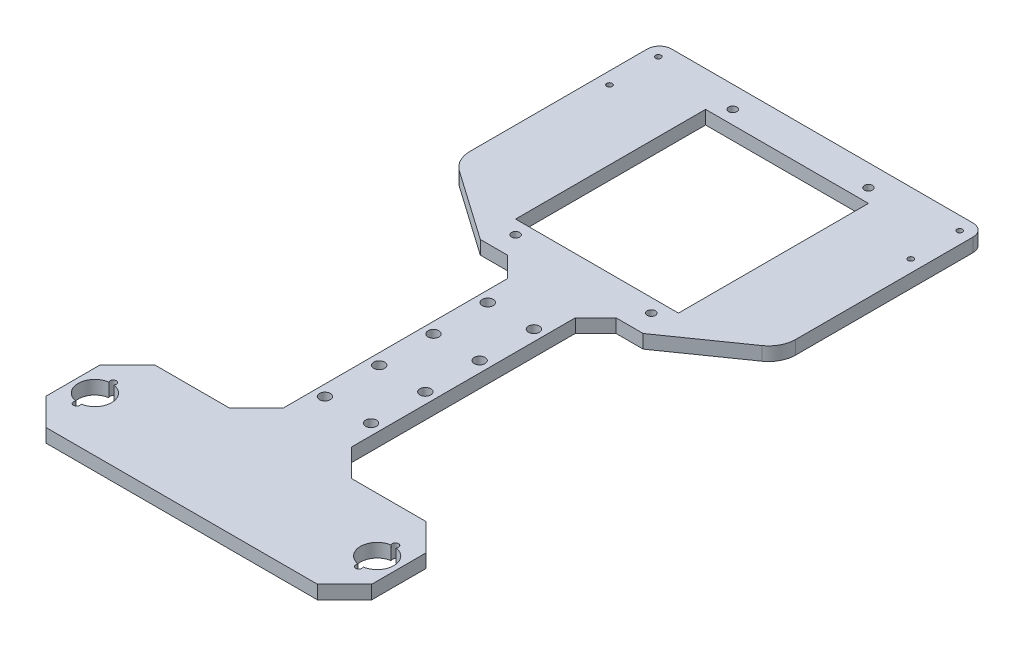
SolidWorks part; units mm, degrees
material "Acrílico (médio-alto impacto)"
ref_plane "Plano frontal" through (0, 0, 0) normal (0, 0, 1) x (1, 0, 0)
ref_plane "Plano superior" through (0, 0, 0) normal (0, 1, 0) x (1, 0, 0)
ref_plane "Plano direito" through (0, 0, 0) normal (1, 0, 0) x (0, 0, -1)
sketch "Esboço1" plane through (0, 0, 0) normal (0, 1, 0) x (1, 0, 0)
  line L0 (-18.0889, 17.9415) -> (-18.0889, 19.4415)
  line L1 (-13.5889, 23.9415) -> (97.4111, 23.9415)
  line L2 (-18.0889, 17.9415) -> (-18.0889, -45.8529)
  line L3 (-13.8247, -54.0444) -> (11.9111, -72.0648)
  line L4 (11.9111, -72.0648) -> (21.9111, -72.0648)
  line L5 (41.9111, -1077.9191) -> (41.9111, -72.0648) construction
  line L7 (97.6469, -54.0444) -> (71.9111, -72.0648)
  line L9 (101.9111, 17.9415) -> (101.9111, -45.8529)
  line L10 (101.9111, 17.9415) -> (101.9111, 19.4415)
  line L11 (21.9111, -72.0648) -> (29.4111, -79.5648)
  line L12 (29.4111, -79.5648) -> (29.4111, -162.0648)
  line L13 (29.4111, -162.0648) -> (19.4111, -172.0648)
  line L14 (19.4111, -172.0648) -> (-8.0889, -172.0648)
  line L15 (-18.0889, -182.0648) -> (-18.0889, -202.0648)
  line L16 (-8.0889, -212.0648) -> (91.9111, -212.0648)
  line L17 (-18.0889, -202.0648) -> (-8.0889, -212.0648)
  line L18 (-8.0889, -172.0648) -> (-18.0889, -182.0648)
  line L19 (71.9111, -72.0648) -> (61.9111, -72.0648)
  line L20 (41.9111, 23.9415) -> (41.9111, 1029.7958) construction
  line L21 (61.9111, -72.0648) -> (54.4111, -79.5648)
  line L22 (91.9111, -172.0648) -> (101.9111, -182.0648)
  line L23 (101.9111, -202.0648) -> (91.9111, -212.0648)
  line L24 (101.9111, -182.0648) -> (101.9111, -202.0648)
  line L25 (64.4111, -172.0648) -> (91.9111, -172.0648)
  line L26 (54.4111, -162.0648) -> (64.4111, -172.0648)
  line L27 (54.4111, -79.5648) -> (54.4111, -162.0648)
  arc A0 (-13.5889, 23.9415) -> (-18.0889, 19.4415) centre (-13.5889, 19.4415) ccw
  arc A1 (97.4111, 23.9415) -> (101.9111, 19.4415) centre (97.4111, 19.4415) cw
  arc A2 (97.6469, -54.0444) -> (101.9111, -45.8529) centre (91.9111, -45.8529) ccw
  arc A3 (-18.0889, -45.8529) -> (-13.8247, -54.0444) centre (-8.0889, -45.8529) ccw
  point P10 (101.9111, -51.0585)
  point P18 (-18.0889, -51.0585)
  point P20 (41.9111, -72.0648)
  point P22 (41.9111, 23.9415)
  point P26 (-18.0889, -212.0648)
  point P28 (-18.0889, -172.0648)
  point P37 (41.9111, -212.0648)
  point P43 (101.9111, -172.0648)
  point P44 (101.9111, -212.0648)
  dimension "D5" = 10
  dimension "D1" = 75
  dimension "D2" = 125
  dimension "D3" = 30
  dimension "D4" = 45
  dimension "D6" = 120
  dimension "D7" = 25
  dimension "D8" = 90
  dimension "D9" = 45
  dimension "D10" = 10
  dimension "D11" = 180
  dimension "D12" = 40
extrude "Base " add sketch "Esboço1" along normal blind 5 contours L9 A2 L7 L19 L21 L27 L26 L25 L22 L24 L23 L16 L17 L15 L18 L14 L13 L12 L11 L4 L3 A3 L2 L0 A0 L1 A1 L10
sketch "Esboço2" plane through (0, 5, 0) normal (0, 1, 0) x (1, 0, 0)
  line L0 (-13.5889, 23.9415) -> (97.4111, 23.9415) construction
  line L1 (-18.0889, -45.8529) -> (-18.0889, 19.4415) construction
  line L2 (41.9111, 23.9415) -> (41.9111, -27.3922) construction
  circle A0 centre (-13.5889, 19.0215) radius 1
  circle A1 centre (-13.5889, 1.0215) radius 1
  circle A2 centre (97.4111, 1.0215) radius 1
  circle A3 centre (97.4111, 19.0215) radius 1
  dimension "D1" = 4.92
  dimension "D2" = 4.5
  dimension "D3" = 2
  dimension "D4" = 2
  dimension "D5" = 4.5
  dimension "D6" = 18
extrude "Furo Bracket Motor" cut sketch "Esboço2" against normal blind 3
sketch "Esboço4" plane through (0, 0, 0) normal (0, -1, 0) x (1, 0, 0)
  line L1 (11.9111, 59.0635) -> (71.9111, 59.0635)
  line L2 (11.9111, 59.0635) -> (11.9111, -10.9365)
  line L3 (11.9111, -10.9365) -> (71.9111, -10.9365)
  line L4 (71.9111, 59.0635) -> (71.9111, -10.9365)
  line L5 (101.9111, -19.4415) -> (101.9111, 45.8529) construction
  line L7 (-13.5889, -23.9415) -> (97.4111, -23.9415) construction
  line L8 (-18.0889, -19.4415) -> (-18.0889, 45.8529) construction
  dimension "D1" = 60
  dimension "D2" = 70
  dimension "D3" = 30
  dimension "D4" = 13.005
  dimension "D5" = 30
extrude "Encaixe PCB" cut sketch "Esboço4" against normal through all
sketch "Esboço6" plane through (0, 0, 0) normal (0, -1, 0) x (1, 0, 0)
  line L0 (71.9111, 59.0635) -> (11.9111, 59.0635) construction
  line L1 (11.9111, 59.0635) -> (11.9111, -10.9365) construction
  line L2 (71.9111, -10.9365) -> (71.9111, 59.0635) construction
  line L3 (11.9111, -10.9365) -> (71.9111, -10.9365) construction
  circle A0 centre (16.9111, 64.0635) radius 1.5
  circle A1 centre (66.9111, 64.0635) radius 1.5
  circle A2 centre (66.9111, -15.9365) radius 1.5
  circle A3 centre (16.9111, -15.9365) radius 1.5
  dimension "D1" = 5
  dimension "D2" = 5
  dimension "D3" = 5
  dimension "D4" = 5
  dimension "D5" = 5
  dimension "D6" = 5
  dimension "D7" = 5
  dimension "D8" = 5
  dimension "D9" = 3
  dimension "D10" = 3
  dimension "D11" = 3
  dimension "D12" = 3
extrude "Parafuso PCB" cut sketch "Esboço6" against normal through all
sketch "Esboço7" plane through (0, 0, 0) normal (0, -1, 0) x (1, 0, 0)
  line L0 (29.4111, 79.5648) -> (29.4111, 162.0648) construction
  line L1 (41.9111, 212.0648) -> (41.9111, -23.9415) construction
  circle A0 centre (33.4111, 90.8148) radius 2
  circle A1 centre (33.4111, 110.8148) radius 2
  circle A2 centre (33.4111, 130.8148) radius 2
  circle A3 centre (33.4111, 150.8148) radius 2
  circle A4 centre (50.4111, 150.8148) radius 2
  circle A5 centre (50.4111, 130.8148) radius 2
  circle A6 centre (50.4111, 110.8148) radius 2
  circle A7 centre (50.4111, 90.8148) radius 2
  dimension "D1" = 11.25
  dimension "D2" = 20
  dimension "D3" = 20
  dimension "D4" = 20
  dimension "D5" = 11.25
  dimension "D6" = 4
  dimension "D7" = 4
  dimension "D8" = 4
  dimension "D9" = 4
  dimension "D10" = 4
  dimension "D11" = 4
extrude "Enforca Gato" cut sketch "Esboço7" against normal through all
sketch "Esboço8" plane through (0, 0, 0) normal (0, -1, 0) x (1, 0, 0)
  line L0 (41.9111, -23.9415) -> (41.9111, 13.0905) construction
  line L1 (-18.0889, 182.0648) -> (-18.0889, 202.0648) construction
  arc A0 (-11.0298, 185.9872) -> (-9.1479, 185.9872) centre (-10.0889, 185.3348) ccw
  arc A1 (-9.1479, 198.1424) -> (-11.0298, 198.1424) centre (-10.0889, 198.7948) ccw
  arc A2 (-11.0298, 198.1424) -> (-11.0298, 185.9872) centre (-10.0889, 192.0648) ccw
  arc A3 (-9.1479, 185.9872) -> (-9.1479, 198.1424) centre (-10.0889, 192.0648) ccw
  arc A4 (92.9702, 185.9872) -> (92.9702, 198.1424) centre (93.9111, 192.0648) cw
  arc A5 (94.8521, 198.1424) -> (94.8521, 185.9872) centre (93.9111, 192.0648) cw
  arc A6 (92.9702, 198.1424) -> (94.8521, 198.1424) centre (93.9111, 198.7948) cw
  arc A7 (94.8521, 185.9872) -> (92.9702, 185.9872) centre (93.9111, 185.3348) cw
  dimension "D1" = 13.46
  dimension "D2" = 2.29
  dimension "D3" = 2.29
  dimension "D4" = 8
  dimension "D5" = 3.27
  dimension "D6" = 12.3
  dimension "D7" = 6.73
extrude "Corte-extrusão1" cut sketch "Esboço8" against normal blind 10
